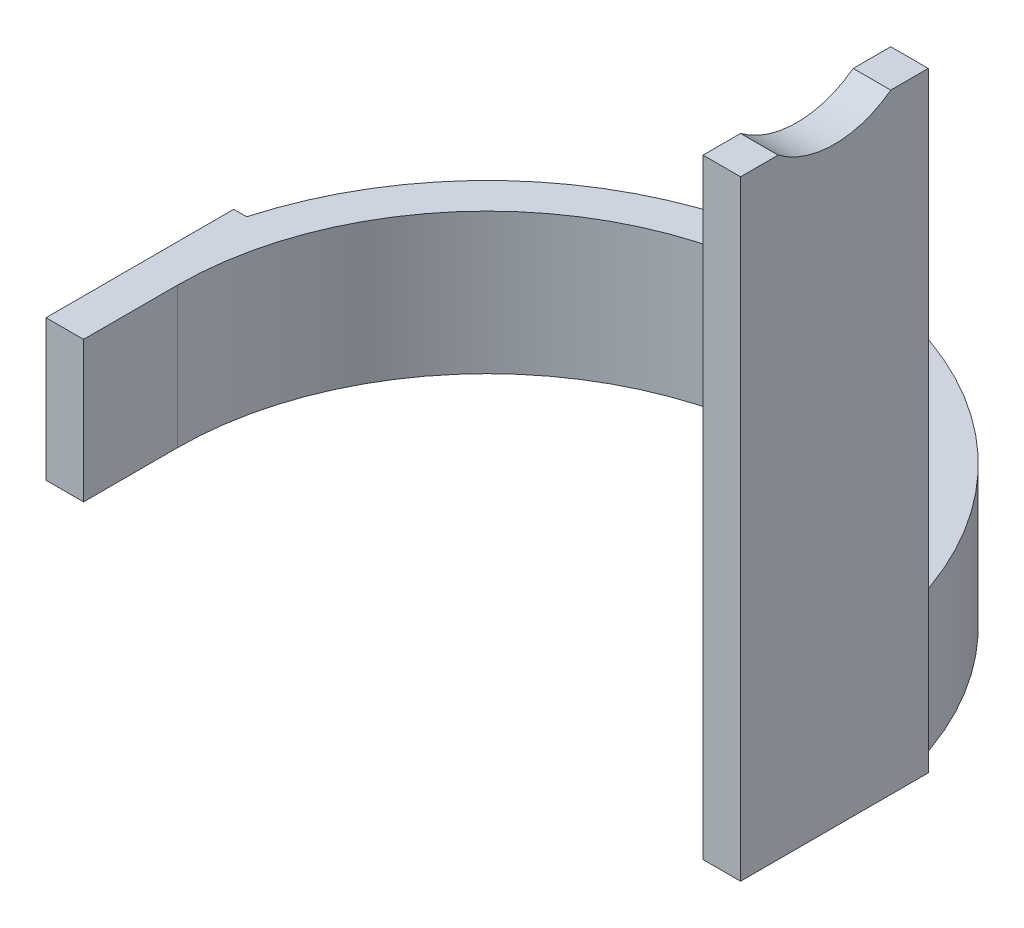
SolidWorks part; units mm, degrees
ref_plane "Front" through (0, 0, 0) normal (0, 0, 1) x (1, 0, 0)
ref_plane "Top" through (0, 0, 0) normal (0, 1, 0) x (1, 0, 0)
ref_plane "Right" through (0, 0, 0) normal (1, 0, 0) x (0, 0, -1)
sketch "草图1" plane through (0, 0, 0) normal (0, 1, 0) x (1, 0, 0)
  line L0 (-72.3418, 0) -> (74, 0) construction
  line L1 (0, 74) -> (0, -74) construction
  line L3 (-74, 20) -> (-71.2461, 20)
  line L4 (-74, 20) -> (-74, -20)
  line L5 (-74, -20) -> (-66, -20)
  line L6 (-66, 0) -> (-66, -20)
  line L7 (74, 20) -> (71.2461, 20)
  line L8 (74, 20) -> (74, -20)
  line L9 (74, -20) -> (66, -20)
  line L10 (66, 0) -> (66, -20)
  arc A0 (71.2461, 20) -> (-71.2461, 20) centre (0, 0) ccw
  arc A1 (66, 0) -> (-66, 0) centre (0, 0) ccw
  dimension "D1" = 40
  dimension "D2" = 20
  dimension "D3" = 8
  dimension "D4" = 8
  dimension "D6" = 40
  dimension "D7" = 20
extrude "凸台-拉伸1" add sketch "草图1" along normal blind 30
sketch "草图2" plane through (0, 30, 0) normal (0, 1, 0) x (1, 0, 0)
  line L1 (-74, -20) -> (-66, -20)
  line L2 (-74, -20) -> (-74, 20)
  line L3 (-74, 20) -> (-66, 20)
  line L4 (-66, -20) -> (-66, 20)
  line L5 (66, -20) -> (74, -20)
  line L6 (66, -20) -> (66, 20)
  line L7 (66, 20) -> (74, 20)
  line L8 (74, -20) -> (74, 20)
  dimension "D1" = 8
extrude "凸台-拉伸2" add sketch "草图2" along normal blind 100
sketch "草图3" plane through (-74, 0, 0) normal (-1, 0, 0) x (0, 0, 1)
  line L0 (-20, 130) -> (20, 130) construction
  circle A0 centre (0, 146) radius 20
  dimension "D1" = 16
extrude "切除-拉伸1" cut sketch "草图3" against normal through all
sketch "草图4" plane through (-74, 0, 0) normal (-1, 0, 0) x (0, 0, 1)
  line L1 (-20, 30) -> (29.7839, 30)
  line L2 (-20, 30) -> (-20, 136.1459)
  line L3 (-20, 136.1459) -> (29.7839, 136.1459)
  line L4 (29.7839, 30) -> (29.7839, 136.1459)
extrude "切除-拉伸3" cut sketch "草图4" against normal blind 10
